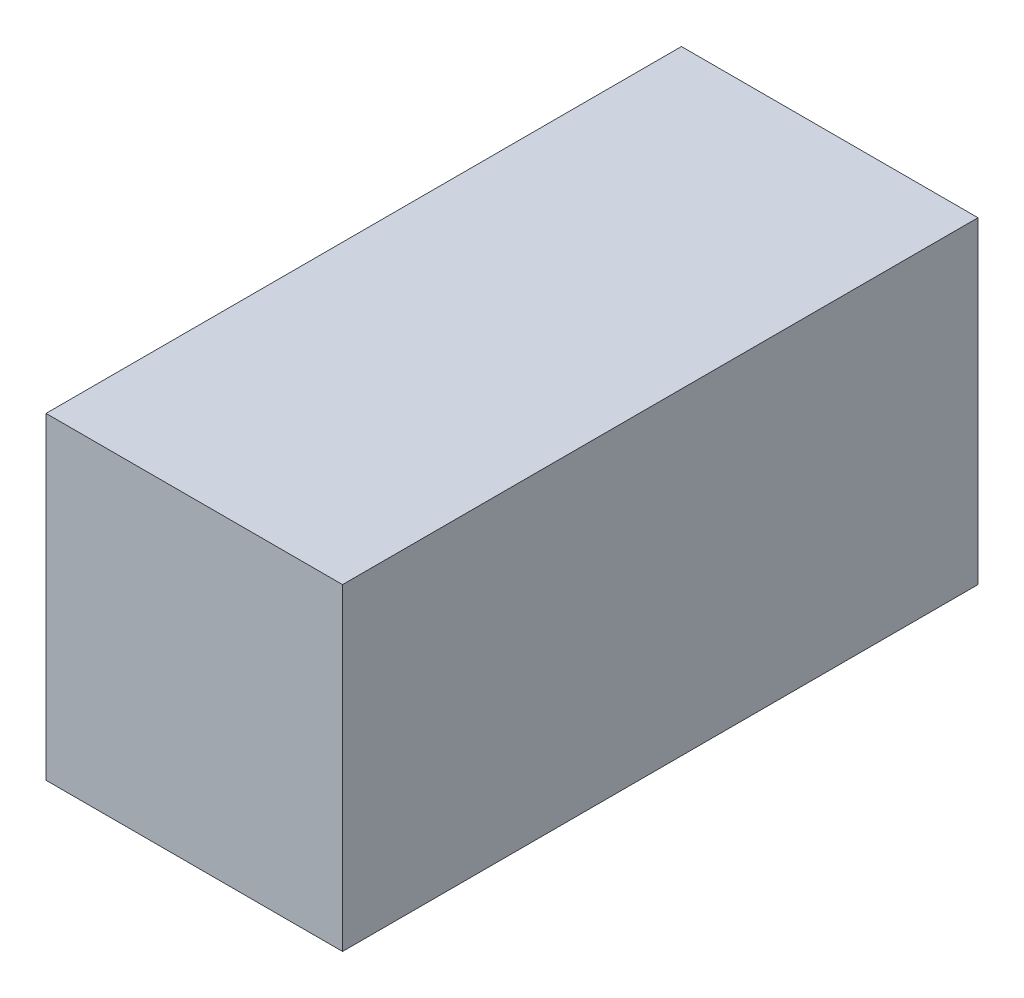
SolidWorks part; units mm, degrees
ref_plane "Front Plane" through (0, 0, 0) normal (0, 0, 1) x (1, 0, 0)
ref_plane "Top Plane" through (0, 0, 0) normal (0, 1, 0) x (1, 0, 0)
ref_plane "Right Plane" through (0, 0, 0) normal (1, 0, 0) x (0, 0, -1)
other "Configuration Table"
sketch "Sketch1" plane through (0, 0, 0) normal (0, 0, 1) x (1, 0, 0)
  line L1 (80, 405) -> (220, 405)
  line L2 (80, 405) -> (80, 555)
  line L3 (80, 555) -> (220, 555)
  line L4 (220, 405) -> (220, 555)
extrude "STORE_klape_kaset_kati_donmus_kap_1_1" add sketch "Sketch1" against normal blind 300 from offset 100 separate body
